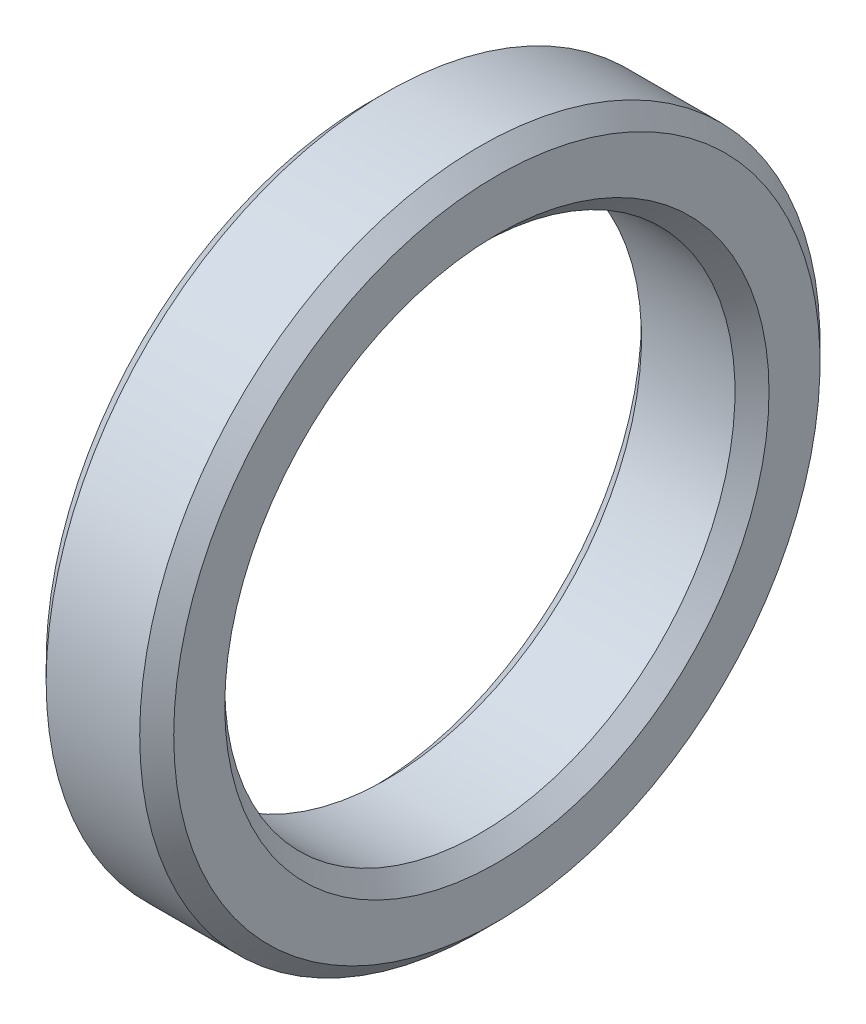
SolidWorks part; units mm, degrees
material "S45C相当"
ref_plane "Front Plane" through (0, 0, 0) normal (0, 0, 1) x (1, 0, 0)
ref_plane "Top Plane" through (0, 0, 0) normal (0, 1, 0) x (1, 0, 0)
ref_plane "Right Plane" through (0, 0, 0) normal (1, 0, 0) x (0, 0, -1)
sketch "Sketch1" plane through (0, 0, 0) normal (0, 0, 1) x (1, 0, 0)
  line L0 (0, 0) -> (1.5, 0) construction
  line L2 (0, 3) -> (1.5, 3)
  line L3 (0, 3) -> (0, 4)
  line L4 (0, 4) -> (1.5, 4)
  line L5 (1.5, 3) -> (1.5, 4)
  dimension "D" = 8
  dimension "V" = 6
  dimension "T" = 1.5
revolve "Revolve1" add sketch "Sketch1" angle 360 about L0
chamfer "Chamfer1" distance 0.2 angle 45 4 edges at (0, 0, 4) (1.5, 0, 4) (1.5, 0, 3) (0, 0, 3)
